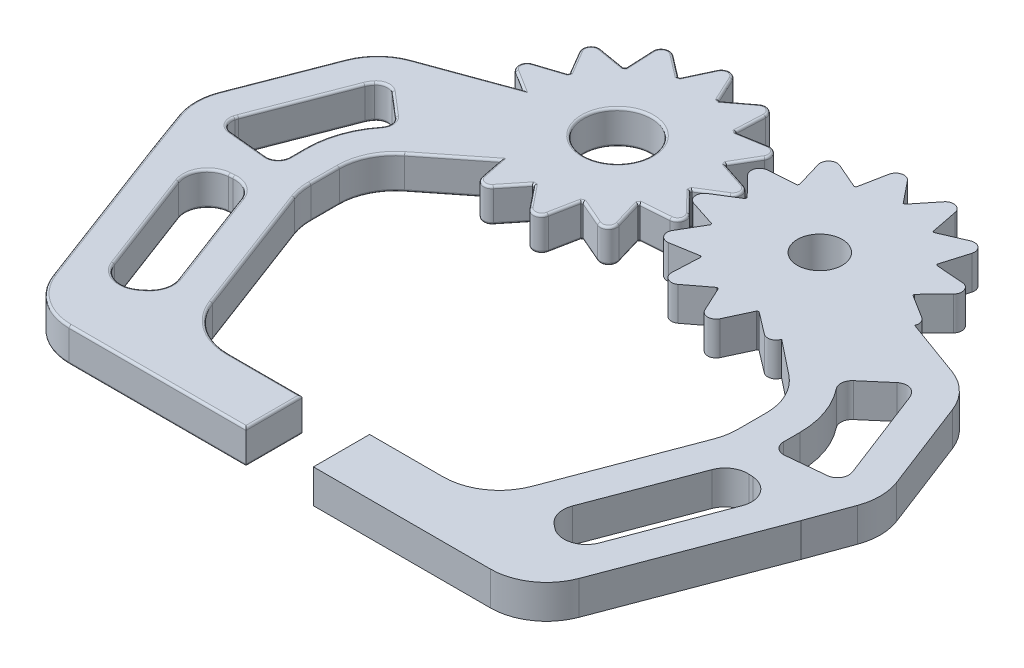
SolidWorks part; units mm, degrees
ref_plane "Front Plane" through (0, 0, 0) normal (0, 0, 1) x (1, 0, 0)
ref_plane "Top Plane" through (0, 0, 0) normal (0, 1, 0) x (1, 0, 0)
ref_plane "Right Plane" through (0, 0, 0) normal (1, 0, 0) x (0, 0, -1)
sketch "Sketch1" plane through (0, 0, 0) normal (0, 1, 0) x (1, 0, 0)
  line L0 (-9, 0) -> (-9, 13.9015) construction
  line L1 (-8.3203, 9.5423) -> (-7.2741, 7.2987)
  line L2 (-9.6797, 9.5423) -> (-10.7259, 7.2987)
  line L3 (-3.9636, 8.1334) -> (-4.0799, 5.6606)
  line L4 (-5.1673, 8.7652) -> (-7.1364, 7.2648)
  line L5 (-0.7607, 4.8612) -> (-2.0128, 2.7257)
  line L6 (-1.533, 5.9801) -> (-3.9737, 5.5666)
  line L7 (0.5547, 0.4754) -> (-1.5465, -0.8336)
  line L8 (0.3908, 1.825) -> (-1.9625, 2.5931)
  line L9 (-0.3188, -4.0193) -> (-2.7876, -4.2019)
  line L10 (0.1633, -2.7482) -> (-1.5636, -0.9744)
  line L11 (-3.1811, -7.5933) -> (-5.4519, -6.6077)
  line L12 (-2.1635, -6.6918) -> (-2.8682, -4.3187)
  line L13 (-7.3764, -9.4277) -> (-8.9291, -7.4997)
  line L14 (-6.0564, -9.1024) -> (-5.5775, -6.6736)
  line L15 (-11.9436, -9.1024) -> (-12.4225, -6.6736)
  line L16 (-10.6236, -9.4277) -> (-9.0709, -7.4997)
  line L17 (-15.8365, -6.6918) -> (-15.1318, -4.3187)
  line L18 (-14.8189, -7.5933) -> (-12.5481, -6.6077)
  line L19 (-18.1633, -2.7482) -> (-16.4364, -0.9744)
  line L20 (-17.6812, -4.0193) -> (-15.2124, -4.2019)
  line L21 (-18.3908, 1.825) -> (-16.0375, 2.5931)
  line L22 (-18.5547, 0.4754) -> (-16.4535, -0.8336)
  line L23 (-16.467, 5.9801) -> (-14.0263, 5.5666)
  line L24 (-17.2393, 4.8612) -> (-15.9872, 2.7257)
  line L25 (-12.8327, 8.7652) -> (-10.8636, 7.2648)
  line L26 (-14.0364, 8.1334) -> (-13.9201, 5.6606)
  circle A0 centre (-9, 0) radius 10 construction
  circle A1 centre (9, 0) radius 10 construction
  arc A2 (-7.1364, 7.2648) -> (-7.2741, 7.2987) centre (-9, 0) ccw
  arc A3 (-8.3203, 9.5423) -> (-9.6797, 9.5423) centre (-9, 9.2253) ccw
  arc A4 (-3.9636, 8.1334) -> (-5.1673, 8.7652) centre (-4.7128, 8.1686) ccw
  arc A5 (-0.7607, 4.8612) -> (-1.533, 5.9801) centre (-1.4077, 5.2406) ccw
  arc A6 (0.5547, 0.4754) -> (0.3908, 1.825) centre (0.1581, 1.112) ccw
  arc A7 (-0.3188, -4.0193) -> (0.1633, -2.7482) centre (-0.3741, -3.2714) ccw
  arc A8 (-3.1811, -7.5933) -> (-2.1635, -6.6918) centre (-2.8825, -6.9053) ccw
  arc A9 (-7.3764, -9.4277) -> (-6.0564, -9.1024) centre (-6.7922, -8.9573) ccw
  arc A10 (-11.9436, -9.1024) -> (-10.6236, -9.4277) centre (-11.2078, -8.9573) ccw
  arc A11 (-15.8365, -6.6918) -> (-14.8189, -7.5933) centre (-15.1175, -6.9053) ccw
  arc A12 (-18.1633, -2.7482) -> (-17.6812, -4.0193) centre (-17.6259, -3.2714) ccw
  arc A13 (-18.3908, 1.825) -> (-18.5547, 0.4754) centre (-18.1581, 1.112) ccw
  arc A14 (-16.467, 5.9801) -> (-17.2393, 4.8612) centre (-16.5923, 5.2406) ccw
  arc A15 (-12.8327, 8.7652) -> (-14.0364, 8.1334) centre (-13.2872, 8.1686) ccw
  arc A16 (-10.7259, 7.2987) -> (-10.8636, 7.2648) centre (-9, 0) ccw
  arc A17 (-13.9201, 5.6606) -> (-14.0263, 5.5666) centre (-9, 0) ccw
  arc A18 (-15.9872, 2.7257) -> (-16.0375, 2.5931) centre (-9, 0) ccw
  arc A19 (-16.4535, -0.8336) -> (-16.4364, -0.9744) centre (-9, 0) ccw
  arc A20 (-15.2124, -4.2019) -> (-15.1318, -4.3187) centre (-9, 0) ccw
  arc A21 (-12.5481, -6.6077) -> (-12.4225, -6.6736) centre (-9, 0) ccw
  arc A22 (-9.0709, -7.4997) -> (-8.9291, -7.4997) centre (-9, 0) ccw
  arc A23 (-5.5775, -6.6736) -> (-5.4519, -6.6077) centre (-9, 0) ccw
  arc A24 (-2.8682, -4.3187) -> (-2.7876, -4.2019) centre (-9, 0) ccw
  arc A25 (-1.5636, -0.9744) -> (-1.5465, -0.8336) centre (-9, 0) ccw
  arc A26 (-1.9625, 2.5931) -> (-2.0128, 2.7257) centre (-9, 0) ccw
  arc A27 (-3.9737, 5.5666) -> (-4.0799, 5.6606) centre (-9, 0) ccw
  point P15 (-9, 11)
  point P75 (-9, 0)
  dimension "D1" = 20
  dimension "D2" = 20
  dimension "D5" = 15
  dimension "D8" = 0.75
  dimension "D3" = 18
  dimension "D4" = 9
  dimension "D6" = 25
  dimension "D7" = 11
  dimension "D9" = 13
extrude "Boss-Extrude1" add sketch "Sketch1" along normal blind 3
sketch "Sketch2" plane through (0, 0, 0) normal (0, 1, 0) x (1, 0, 0)
  line L0 (9, 0) -> (12.5984, 14.6004) construction
  line L1 (11.9434, 9.1024) -> (12.4223, 6.6736)
  line L2 (10.6235, 9.4277) -> (9.0708, 7.4997)
  line L3 (15.8364, 6.6919) -> (15.1317, 4.3188)
  line L4 (14.8188, 7.5934) -> (12.5479, 6.6077)
  line L5 (18.1632, 2.7484) -> (16.4364, 0.9745)
  line L6 (17.6811, 4.0195) -> (15.2123, 4.2021)
  line L7 (18.3908, -1.8248) -> (16.0375, -2.593)
  line L8 (18.5547, -0.4752) -> (16.4535, 0.8337)
  line L9 (16.4672, -5.9799) -> (14.0264, -5.5665)
  line L10 (17.2394, -4.8611) -> (15.9872, -2.7256)
  line L11 (12.8328, -8.7651) -> (10.8638, -7.2647)
  line L12 (14.0366, -8.1333) -> (13.9202, -5.6605)
  line L13 (8.3205, -9.5423) -> (7.2742, -7.2987)
  line L14 (9.6799, -9.5423) -> (10.7261, -7.2987)
  line L15 (3.9638, -8.1335) -> (4.08, -5.6607)
  line L16 (5.1675, -8.7653) -> (7.1365, -7.2648)
  line L17 (0.7608, -4.8614) -> (2.0129, -2.7259)
  line L18 (1.5331, -5.9802) -> (3.9738, -5.5667)
  line L19 (-0.5547, -0.4756) -> (1.5465, 0.8334)
  line L20 (-0.3908, -1.8252) -> (1.9626, -2.5933)
  line L21 (0.3187, 4.0191) -> (2.7875, 4.2018)
  line L22 (-0.1633, 2.748) -> (1.5635, 0.9742)
  line L23 (3.1809, 7.5932) -> (5.4518, 6.6076)
  line L24 (2.1634, 6.6916) -> (2.8681, 4.3185)
  line L25 (7.3762, 9.4277) -> (8.9289, 7.4997)
  line L26 (6.0562, 9.1023) -> (5.5774, 6.6735)
  line L27 (9, 0) -> (9, 20.9978) construction
  arc A0 (5.5774, 6.6735) -> (5.4518, 6.6076) centre (9, 0) ccw
  arc A1 (11.9434, 9.1024) -> (10.6235, 9.4277) centre (11.2076, 8.9573) ccw
  arc A2 (15.8364, 6.6919) -> (14.8188, 7.5934) centre (15.1174, 6.9054) ccw
  arc A3 (18.1632, 2.7484) -> (17.6811, 4.0195) centre (17.6258, 3.2715) ccw
  arc A4 (18.3908, -1.8248) -> (18.5547, -0.4752) centre (18.1581, -1.1118) ccw
  arc A5 (16.4672, -5.9799) -> (17.2394, -4.8611) centre (16.5924, -5.2404) ccw
  arc A6 (12.8328, -8.7651) -> (14.0366, -8.1333) centre (13.2874, -8.1686) ccw
  arc A7 (8.3205, -9.5423) -> (9.6799, -9.5423) centre (9.0002, -9.2253) ccw
  arc A8 (3.9638, -8.1335) -> (5.1675, -8.7653) centre (4.7129, -8.1687) ccw
  arc A9 (0.7608, -4.8614) -> (1.5331, -5.9802) centre (1.4078, -5.2407) ccw
  arc A10 (-0.5547, -0.4756) -> (-0.3908, -1.8252) centre (-0.1581, -1.1122) ccw
  arc A11 (0.3187, 4.0191) -> (-0.1633, 2.748) centre (0.3741, 3.2712) ccw
  arc A12 (3.1809, 7.5932) -> (2.1634, 6.6916) centre (2.8823, 6.9051) ccw
  arc A13 (7.3762, 9.4277) -> (6.0562, 9.1023) centre (6.792, 8.9572) ccw
  arc A14 (2.8681, 4.3185) -> (2.7875, 4.2018) centre (9, 0) ccw
  arc A15 (1.5635, 0.9742) -> (1.5465, 0.8334) centre (9, 0) ccw
  arc A16 (1.9626, -2.5933) -> (2.0129, -2.7259) centre (9, 0) ccw
  arc A17 (3.9738, -5.5667) -> (4.08, -5.6607) centre (9, 0) ccw
  arc A18 (7.1365, -7.2648) -> (7.2742, -7.2987) centre (9, 0) ccw
  arc A19 (10.7261, -7.2987) -> (10.8638, -7.2647) centre (9, 0) ccw
  arc A20 (13.9202, -5.6605) -> (14.0264, -5.5665) centre (9, 0) ccw
  arc A21 (15.9872, -2.7256) -> (16.0375, -2.593) centre (9, 0) ccw
  arc A22 (16.4535, 0.8337) -> (16.4364, 0.9745) centre (9, 0) ccw
  arc A23 (15.2123, 4.2021) -> (15.1317, 4.3188) centre (9, 0) ccw
  arc A24 (12.5479, 6.6077) -> (12.4223, 6.6736) centre (9, 0) ccw
  arc A25 (9.0708, 7.4997) -> (8.9289, 7.4997) centre (9, 0) ccw
  point P11 (11.6323, 10.6804)
  point P73 (9, 0)
  dimension "D1" = 15
  dimension "D2" = 25
  dimension "D4" = 0.75
  dimension "D3" = 11
  dimension "D6" = 13.845
  dimension "D5" = 13
extrude "Boss-Extrude2" add sketch "Sketch2" along normal blind 3 separate body
sketch "Sketch3" plane through (0, 3, 0) normal (0, 1, 0) x (1, 0, 0)
  circle A0 centre (-9, 0) radius 3
  dimension "D1" = 6
extrude "Cut-Extrude1" cut sketch "Sketch3" against normal blind 3
sketch "Sketch4" plane through (0, 3, 0) normal (0, 1, 0) x (1, 0, 0)
  line L0 (-12, 0) -> (-15, 0)
  line L1 (-15, 0) -> (-24.0634, -3.2988)
  line L2 (-30.1807, -17.8135) -> (-28.8453, -21.4827)
  line L3 (-18.7439, -39.0643) -> (-3, -39.0643)
  line L4 (-12, -5.2004) -> (-11.2334, -6.1968)
  line L5 (-11.2334, -6.1968) -> (-17.0992, -10.8467)
  line L6 (-18.9932, -14.765) -> (-18.9932, -17.308)
  line L7 (-18.6701, -19.0761) -> (-14.2257, -30.8324)
  line L8 (-3, -34.0643) -> (-3, -39.0643)
  line L9 (-12, 0) -> (-12, -5.2004)
  line L10 (-9.5488, -34.0643) -> (-3, -34.0643)
  line L11 (-27.0179, -6.1968) -> (-30.1468, -14.3029)
  line L12 (-23.4209, -35.8324) -> (-28.8237, -21.5407)
  line L13 (0, 0) -> (0, 23.1588) construction
  line L14 (23.4209, -35.8324) -> (28.8237, -21.5407)
  line L15 (27.0179, -6.1968) -> (30.1468, -14.3029)
  line L16 (9.5488, -34.0643) -> (3, -34.0643)
  line L17 (12, 0) -> (12, -5.2004)
  line L18 (3, -34.0643) -> (3, -39.0643)
  line L19 (18.6701, -19.0761) -> (14.2257, -30.8324)
  line L20 (18.9932, -14.765) -> (18.9932, -17.308)
  line L21 (11.2334, -6.1968) -> (17.0992, -10.8467)
  line L22 (12, -5.2004) -> (11.2334, -6.1968)
  line L23 (18.7439, -39.0643) -> (3, -39.0643)
  line L24 (30.1807, -17.8135) -> (28.8453, -21.4827)
  line L25 (15, 0) -> (24.0634, -3.2988)
  line L26 (12, 0) -> (15, 0)
  line L27 (-24.2191, -7.2771) -> (-27.3481, -15.3832)
  line L28 (-21.9932, -14.765) -> (-21.9932, -17.308) construction
  line L29 (-21.9932, -14.765) -> (-21.9932, -16.2063)
  line L30 (-22.4737, -6.6004) -> (-20.3791, -8.3936)
  line L31 (-26.5513, -16.866) -> (-23.0897, -17.2017)
  line L32 (-13.097, -3.8458) -> (-18.9628, -8.4958) construction
  line L33 (-21.5893, -32.1934) -> (-25.0724, -22.9801)
  line L34 (-20.9471, -21.5367) -> (-17.5451, -30.5358)
  line L35 (-23.3522, -20.2786) -> (-22.9685, -20.2496)
  line L36 (-18.1633, -32.8022) -> (-18.466, -33.0453)
  line L37 (-21.4763, -20.1369) -> (-17.0319, -31.8932) construction
  line L38 (-20.6147, -34.7715) -> (-26.0176, -20.4798) construction
  line L39 (21.5893, -32.1934) -> (25.0724, -22.9801)
  line L40 (24.2191, -7.2771) -> (27.3481, -15.3832)
  line L41 (22.4737, -6.6004) -> (20.3791, -8.3936)
  line L42 (23.3522, -20.2786) -> (22.9685, -20.2496)
  line L43 (26.5513, -16.866) -> (23.0897, -17.2017)
  line L44 (21.9932, -14.765) -> (21.9932, -16.2063)
  line L45 (18.1633, -32.8022) -> (18.466, -33.0453)
  line L46 (20.9471, -21.5367) -> (17.5451, -30.5358)
  circle A0 centre (-9, 0) radius 3 construction
  arc A1 (-17.0992, -10.8467) -> (-18.9932, -14.765) centre (-13.9932, -14.765) ccw
  arc A2 (-27.0179, -6.1968) -> (-24.0634, -3.2988) centre (-22.3533, -7.9973) cw
  arc A3 (-14.2257, -30.8324) -> (-9.5488, -34.0643) centre (-9.5488, -29.0643) ccw
  arc A4 (-23.4209, -35.8324) -> (-18.7439, -39.0643) centre (-18.7439, -34.0643) ccw
  arc A5 (-28.8237, -21.5407) -> (-28.8453, -21.4827) centre (-24.1468, -19.7726) cw
  arc A6 (-18.9932, -17.308) -> (-18.6701, -19.0761) centre (-13.9932, -17.308) ccw
  arc A7 (-30.1468, -14.3029) -> (-30.1807, -17.8135) centre (-25.4823, -16.1034) ccw
  arc A8 (30.1468, -14.3029) -> (30.1807, -17.8135) centre (25.4823, -16.1034) cw
  arc A9 (18.9932, -17.308) -> (18.6701, -19.0761) centre (13.9932, -17.308) cw
  arc A10 (28.8237, -21.5407) -> (28.8453, -21.4827) centre (24.1468, -19.7726) ccw
  arc A11 (23.4209, -35.8324) -> (18.7439, -39.0643) centre (18.7439, -34.0643) cw
  arc A12 (14.2257, -30.8324) -> (9.5488, -34.0643) centre (9.5488, -29.0643) cw
  arc A13 (27.0179, -6.1968) -> (24.0634, -3.2988) centre (22.3533, -7.9973) ccw
  arc A14 (17.0992, -10.8467) -> (18.9932, -14.765) centre (13.9932, -14.765) cw
  arc A15 (-24.2191, -7.2771) -> (-23.8947, -6.7229) centre (-22.3533, -7.9973) cw
  arc A16 (-27.3481, -15.3832) -> (-27.4274, -15.638) centre (-25.4823, -16.1034) ccw
  arc A17 (-20.2476, -9.7768) -> (-21.9932, -14.765) centre (-13.9932, -14.765) ccw
  arc A18 (-27.3481, -15.3832) -> (-27.3617, -16.7874) centre (-25.4823, -16.1034) ccw construction
  arc A19 (-18.9628, -8.4958) -> (-21.9932, -14.765) centre (-13.9932, -14.765) ccw construction
  arc A20 (-27.4274, -15.638) -> (-26.5513, -16.866) centre (-26.4548, -15.8707) ccw
  arc A21 (-21.9932, -16.2063) -> (-23.0897, -17.2017) centre (-22.9932, -16.2063) cw
  arc A22 (-20.3791, -8.3936) -> (-20.2476, -9.7768) centre (-21.0294, -9.1533) cw
  arc A23 (-24.2191, -7.2771) -> (-23.0374, -6.1179) centre (-22.3533, -7.9973) cw construction
  arc A24 (-23.8947, -6.7229) -> (-22.4737, -6.6004) centre (-23.124, -7.3601) cw
  arc A25 (-17.5451, -30.5358) -> (-18.1633, -32.8022) centre (-19.4159, -31.243) cw
  arc A26 (-20.9471, -21.5367) -> (-22.9685, -20.2496) centre (-22.8179, -22.2439) ccw
  arc A27 (-25.0724, -22.9801) -> (-23.3522, -20.2786) centre (-23.2016, -22.2729) cw
  arc A28 (-21.5893, -32.1934) -> (-18.466, -33.0453) centre (-19.7186, -31.4862) ccw
  arc A29 (23.8947, -6.7229) -> (22.4737, -6.6004) centre (23.124, -7.3601) ccw
  arc A30 (20.3791, -8.3936) -> (20.2476, -9.7768) centre (21.0294, -9.1533) ccw
  arc A31 (24.2191, -7.2771) -> (23.8947, -6.7229) centre (22.3533, -7.9973) ccw
  arc A32 (25.0724, -22.9801) -> (23.3522, -20.2786) centre (23.2016, -22.2729) ccw
  arc A33 (20.9471, -21.5367) -> (22.9685, -20.2496) centre (22.8179, -22.2439) cw
  arc A34 (21.9932, -16.2063) -> (23.0897, -17.2017) centre (22.9932, -16.2063) ccw
  arc A35 (27.4274, -15.638) -> (26.5513, -16.866) centre (26.4548, -15.8707) cw
  arc A36 (20.2476, -9.7768) -> (21.9932, -14.765) centre (13.9932, -14.765) cw
  arc A37 (21.5893, -32.1934) -> (18.466, -33.0453) centre (19.7186, -31.4862) cw
  arc A38 (17.5451, -30.5358) -> (18.1633, -32.8022) centre (19.4159, -31.243) ccw
  arc A39 (27.3481, -15.3832) -> (27.4274, -15.638) centre (25.4823, -16.1034) cw
  dimension "D6" = 5
  dimension "D7" = 5
  dimension "D10" = 1
  dimension "D13" = 2
  dimension "D1" = 3
  dimension "D2" = 5
  dimension "D3" = 3
  dimension "D4" = 20
  dimension "D5" = 90
  dimension "D8" = 3
  dimension "D9" = 3
  dimension "D11" = 3
  dimension "D12" = 3
extrude "Boss-Extrude3" add sketch "Sketch4" against normal blind 3
sketch "Sketch5" plane through (0, 3, 0) normal (0, 1, 0) x (1, 0, 0)
  circle A0 centre (9, 0) radius 2
  dimension "D1" = 4
extrude "Cut-Extrude2" cut sketch "Sketch5" against normal blind 10
fillet "Fillet1" radius 0.2 160 edges at (-20.2449, 0, 33.4157) (-23.3308, 0, 27.5868) (-24.8886, 0, 21.1987) (-23.1603, 0, 20.2641) (-21.7437, 0, 20.5569) (-19.2461, 0, 26.0362) (-17.4864, 0, 31.7693) (-18.3146, 0, 32.9237) (-25.7836, 0, 11.3301) (-24.0793, 0, 6.9869) (-23.2099, 0, 6.3638) (-21.4264, 0, 7.497) (-20.0339, 0, 9.0586) (-21.5442, 0, 12.1226) (-21.9932, 0, 15.4856) (-22.321, 0, 16.9468) (-24.8205, 0, 17.0338) (-27.2689, 0, 16.4514) (-27.392, 0, 15.5093) (-25.8545, 0, 4.4278) (-28.5824, 0, 10.2498) (-30.482, 0, 16.0551) (-29.513, 0, 19.6481) (-28.8346, 0, 21.5117) (-26.1223, 0, 28.6865) (-21.5864, 0, 38.1777) (-10.872, 0, 39.0643) (-3, 0, 36.5643) (-6.2744, 0, 34.0643) (-12.3913, 0, 33.1777) (-16.4479, 0, 24.9542) (-18.9117, 0, 18.2067) (-18.9932, 0, 16.0365) (-18.4948, 0, 12.589) (-14.7211, 0, 8.9616) (-12.1433, 3, 8.0894) (-12.1433, 0, 8.0894) (-11.3873, 0, 9.6855) (-11.3873, 3, 9.6855) (-9.8473, 0, 8.4637) (-9.8473, 3, 8.4637) (-9, 0, 7.5) (-9, 3, 7.5) (-8.1527, 0, 8.4637) (-8.1527, 3, 8.4637) (-6.6127, 0, 9.6855) (-6.6127, 3, 9.6855) (-5.817, 0, 7.888) (-5.817, 3, 7.888) (-5.5146, 0, 6.6409) (-5.5146, 3, 6.6409) (-4.3165, 0, 7.1005) (-4.3165, 3, 7.1005) (-2.3851, 0, 7.4667) (-2.3851, 3, 7.4667) (-2.5158, 0, 5.5052) (-2.5158, 3, 5.5052) (-2.8276, 0, 4.2605) (-2.8276, 3, 4.2605) (-1.5532, 0, 4.1106) (-1.5532, 3, 4.1106) (0.3271, 0, 3.5373) (0.3271, 3, 3.5373) (-0.7002, 0, 1.8613) (-0.7002, 3, 1.8613) (-1.5547, 0, 0.904) (-1.5547, 3, 0.904) (-0.4959, 0, 0.1791) (-0.4959, 3, 0.1791) (0.9026, 0, -1.2024) (0.9026, 3, -1.2024) (-0.7859, 0, -2.209) (-0.7859, 3, -2.209) (-1.9874, 0, -2.6595) (-1.9874, 3, -2.6595) (-1.3868, 0, -3.7935) (-1.3868, 3, -3.7935) (-0.7904, 0, -5.6666) (-0.7904, 3, -5.6666) (-2.7533, 0, -5.7733) (-2.7533, 3, -5.7733) (-4.0266, 0, -5.6138) (-4.0266, 3, -5.6138) (-4.0217, 0, -6.897) (-4.0217, 3, -6.897) (-4.3642, 0, -8.8327) (-4.3642, 3, -8.8327) (-6.1519, 0, -8.015) (-6.1519, 3, -8.015) (-7.2051, 0, -7.2821) (-7.2051, 3, -7.2821) (-7.7972, 0, -8.4205) (-7.7972, 3, -8.4205) (-9, 0, -9.9753) (-9, 3, -9.9753) (-10.2028, 0, -8.4205) (-10.2028, 3, -8.4205) (-10.7949, 0, -7.2821) (-10.7949, 3, -7.2821) (-11.8481, 0, -8.015) (-11.8481, 3, -8.015) (-13.6358, 0, -8.8327) (-13.6358, 3, -8.8327) (-13.9783, 0, -6.897) (-13.9783, 3, -6.897) (-13.9734, 0, -5.6138) (-13.9734, 3, -5.6138) (-15.2467, 0, -5.7733) (-15.2467, 3, -5.7733) (-17.2096, 0, -5.6666) (-17.2096, 3, -5.6666) (-16.6132, 0, -3.7935) (-16.6132, 3, -3.7935) (-16.0126, 0, -2.6595) (-16.0126, 3, -2.6595) (-17.2141, 0, -2.209) (-17.2141, 3, -2.209) (-18.9026, 0, -1.2024) (-18.9026, 3, -1.2024) (-17.6584, 0, 0.083) (-17.6584, 3, 0.083) (-20.4128, 0, 1.9701) (-9, 0, 3) (-9, 3, 3) (-24.8205, 3, 17.0338) (-22.321, 3, 16.9468) (-21.9932, 3, 15.4856) (-21.5442, 3, 12.1226) (-20.0339, 3, 9.0586) (-21.4264, 3, 7.497) (-23.2099, 3, 6.3638) (-24.0793, 3, 6.9869) (-25.7836, 3, 11.3301) (-27.392, 3, 15.5093) (-27.2689, 3, 16.4514) (-19.2461, 3, 26.0362) (-21.7437, 3, 20.5569) (-23.1603, 3, 20.2641) (-24.8886, 3, 21.1987) (-23.3308, 3, 27.5868) (-20.2449, 3, 33.4157) (-18.3146, 3, 32.9237) (-17.4864, 3, 31.7693) (-14.7211, 3, 8.9616) (-18.4948, 3, 12.589) (-18.9932, 3, 16.0365) (-18.9117, 3, 18.2067) (-16.4479, 3, 24.9542) (-12.3913, 3, 33.1777) (-6.2744, 3, 34.0643) (-3, 3, 36.5643) (-10.872, 3, 39.0643) (-21.5864, 3, 38.1777) (-26.1223, 3, 28.6865) (-28.8346, 3, 21.5117) (-29.513, 3, 19.6481) (-30.482, 3, 16.0551) (-28.5824, 3, 10.2498) (-25.8545, 3, 4.4278) (-20.4128, 3, 1.9701)
